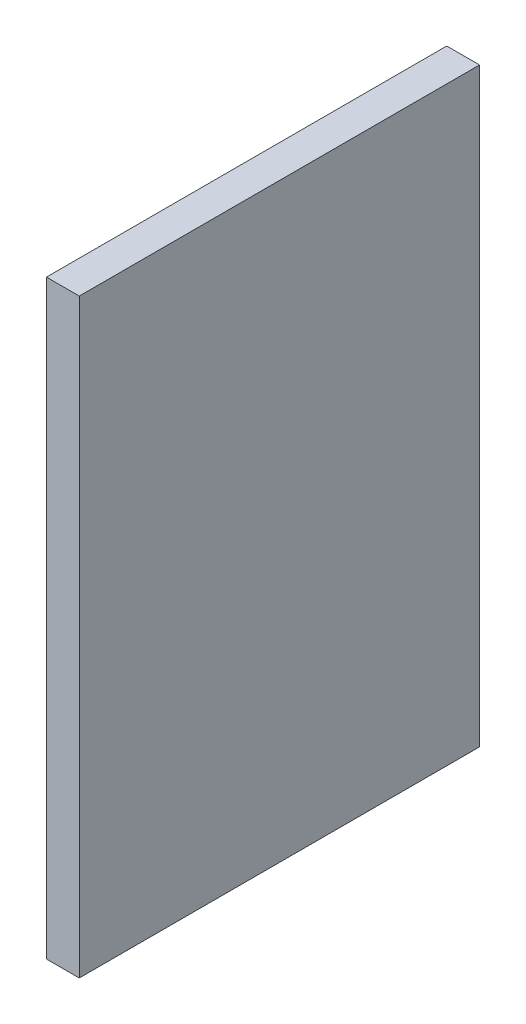
SolidWorks part; units mm, degrees
ref_plane "Front Plane" through (0, 0, 0) normal (0, 0, 1) x (1, 0, 0)
ref_plane "Top Plane" through (0, 0, 0) normal (0, 1, 0) x (1, 0, 0)
ref_plane "Right Plane" through (0, 0, 0) normal (1, 0, 0) x (0, 0, -1)
sketch "Sketch1" plane through (0, 0, 0) normal (1, 0, 0) x (0, 0, -1)
  line L1 (0, 0) -> (77.47, 0)
  line L2 (0, 0) -> (0, 114.3)
  line L3 (0, 114.3) -> (77.47, 114.3)
  line L4 (77.47, 0) -> (77.47, 114.3)
  dimension "D1" = 77.47
  dimension "D2" = 114.3
extrude "Boss-Extrude1" add sketch "Sketch1" along normal blind 6.35
